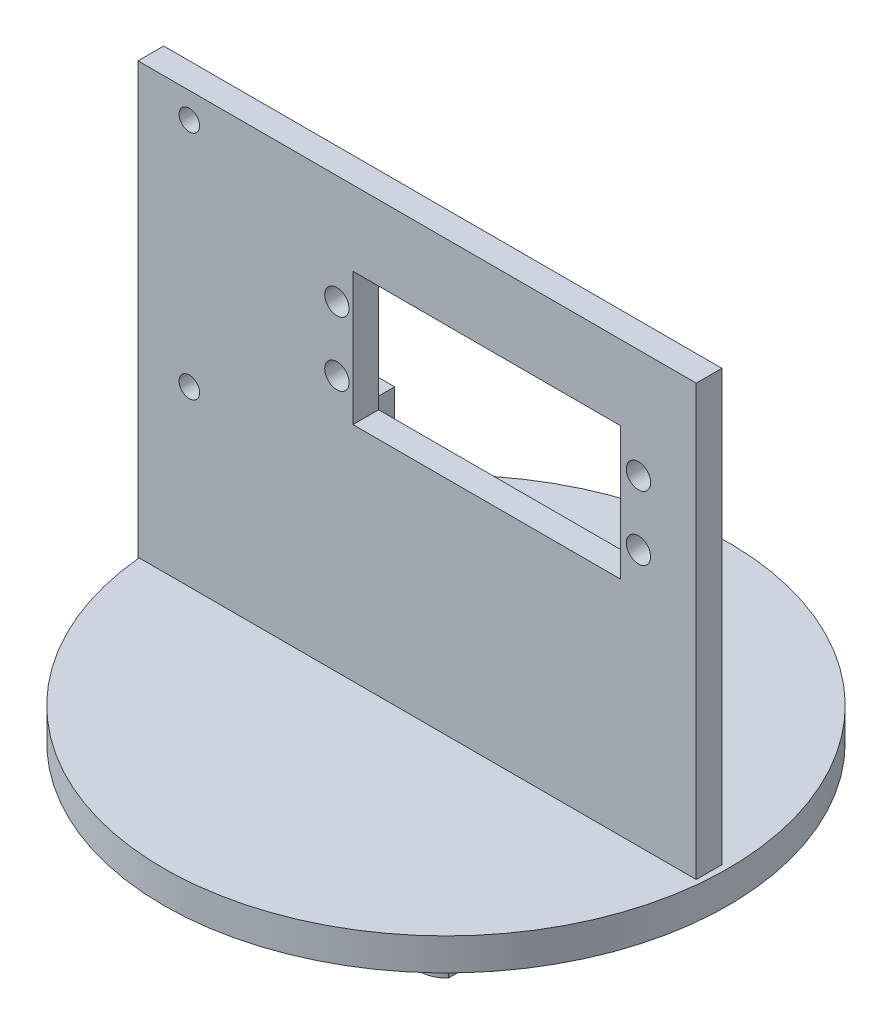
SolidWorks part; units mm, degrees
ref_plane "Front Plane" through (0, 0, 0) normal (0, 0, 1) x (1, 0, 0)
ref_plane "Top Plane" through (0, 0, 0) normal (0, 1, 0) x (1, 0, 0)
ref_plane "Right Plane" through (0, 0, 0) normal (1, 0, 0) x (0, 0, -1)
sketch "Yaw_platform_profile" plane through (0, 0, 0) normal (0, 1, 0) x (1, 0, 0)
  circle A0 centre (0, 0) radius 44
  dimension "D1" = 88
extrude "Yaw_platform" add sketch "Yaw_platform_profile" along normal blind 5 from offset 72
sketch "Printed_hollow_yaw_spindle_profile" plane through (0, 0, 0) normal (0, 1, 0) x (1, 0, 0)
  circle A0 centre (0, 0) radius 3.95
  circle A1 centre (0, 0) radius 1.75
  dimension "D1" = 7.9
  dimension "D2" = 3.5
extrude "Printed_hollow_yaw_spindle" add sketch "Printed_hollow_yaw_spindle_profile" along normal blind 29 from offset 43
sketch "Inner_race_load_shoulder_profile" plane through (0, 0, 0) normal (0, 1, 0) x (1, 0, 0)
  circle A0 centre (0, 0) radius 6
  circle A1 centre (0, 0) radius 1.75
  dimension "D1" = 12
  dimension "D2" = 3.5
extrude "Inner_race_load_shoulder" add sketch "Inner_race_load_shoulder_profile" along normal blind 2 from offset 70
sketch "D_flat_drive_key_profile" plane through (0, 0, 0) normal (0, 1, 0) x (1, 0, 0)
  line L1 (3, -5) -> (6, -5)
  line L2 (3, -5) -> (3, 5)
  line L3 (3, 5) -> (6, 5)
  line L4 (6, -5) -> (6, 5)
  dimension "D1" = 3
  dimension "D2" = 10
  dimension "D3" = 3
  dimension "D4" = 5
extrude "D_flat_on_spindle_end" cut sketch "D_flat_drive_key_profile" along normal blind 5 from offset 43
sketch "Shoulder_mount_plate_profile" plane through (0, 0, 0) normal (0, 0, 1) x (1, 0, 0)
  line L1 (-44, 76) -> (43, 76)
  line L2 (-44, 76) -> (-44, 144)
  line L3 (-44, 144) -> (43, 144)
  line L4 (43, 76) -> (43, 144)
  dimension "D1" = 87
  dimension "D2" = 68
  dimension "D3" = 43
  dimension "D4" = 76
extrude "Shoulder_mount_plate" add sketch "Shoulder_mount_plate_profile" along normal blind 4
sketch "MG996_body_window_profile" plane through (0, 0, 0) normal (0, 0, 1) x (1, 0, 0)
  line L1 (-10.5, 111.65) -> (31.2, 111.65)
  line L2 (-10.5, 111.65) -> (-10.5, 132.35)
  line L3 (-10.5, 132.35) -> (31.2, 132.35)
  line L4 (31.2, 111.65) -> (31.2, 132.35)
  dimension "D1" = 41.7
  dimension "D2" = 20.7
  dimension "D3" = 31.2
  dimension "D4" = 111.65
extrude "MG996_body_window" cut sketch "MG996_body_window_profile" along normal through all from offset 5
sketch "MG996_tab_mounts_profile" plane through (0, 0, 0) normal (0, 0, 1) x (1, 0, 0)
  circle A0 centre (-13, 117) radius 1.9
  circle A1 centre (-13, 127) radius 1.9
  circle A2 centre (34, 117) radius 1.9
  circle A3 centre (34, 127) radius 1.9
  dimension "D1" = 3.8
  dimension "D2" = 3.8
  dimension "D3" = 3.8
  dimension "D4" = 3.8
  dimension "D5" = 34
  dimension "D6" = 13
  dimension "D7" = 117
  dimension "D8" = 127
extrude "MG996_tab_mounts" cut sketch "MG996_tab_mounts_profile" along normal through all from offset 50
sketch "Passive_shoulder_standoffs_profile" plane through (0, 0, 0) normal (0, 0, 1) x (1, 0, 0)
  circle A0 centre (-36, 104) radius 1.6
  circle A1 centre (-36, 140) radius 1.6
  dimension "D1" = 3.2
  dimension "D2" = 3.2
  dimension "D3" = 36
  dimension "D4" = 104
  dimension "D5" = 140
extrude "Passive_shoulder_standoffs" cut sketch "Passive_shoulder_standoffs_profile" along normal through all from offset 50
sketch "Upright_rib_profile" plane through (0, 0, 0) normal (0, 0, 1) x (1, 0, 0)
  line L1 (-23, 77) -> (-16, 77)
  line L2 (-23, 77) -> (-23, 108)
  line L3 (-23, 108) -> (-16, 108)
  line L4 (-16, 77) -> (-16, 108)
  dimension "D1" = 7
  dimension "D2" = 31
  dimension "D3" = 16
  dimension "D4" = 77
extrude "Upright_rib" add sketch "Upright_rib_profile" along normal blind 12 from offset 8
sketch "Yaw_positive_retention_crossbolt_profile" plane through (0, 0, 0) normal (1, 0, 0) x (0, 0, -1)
  circle A0 centre (0, 45.5) radius 1.1
  dimension "D1" = 2.2
  dimension "D2" = 45.5
extrude "Yaw_positive_retention_crossbolt" cut sketch "Yaw_positive_retention_crossbolt_profile" along normal through all from offset 10
